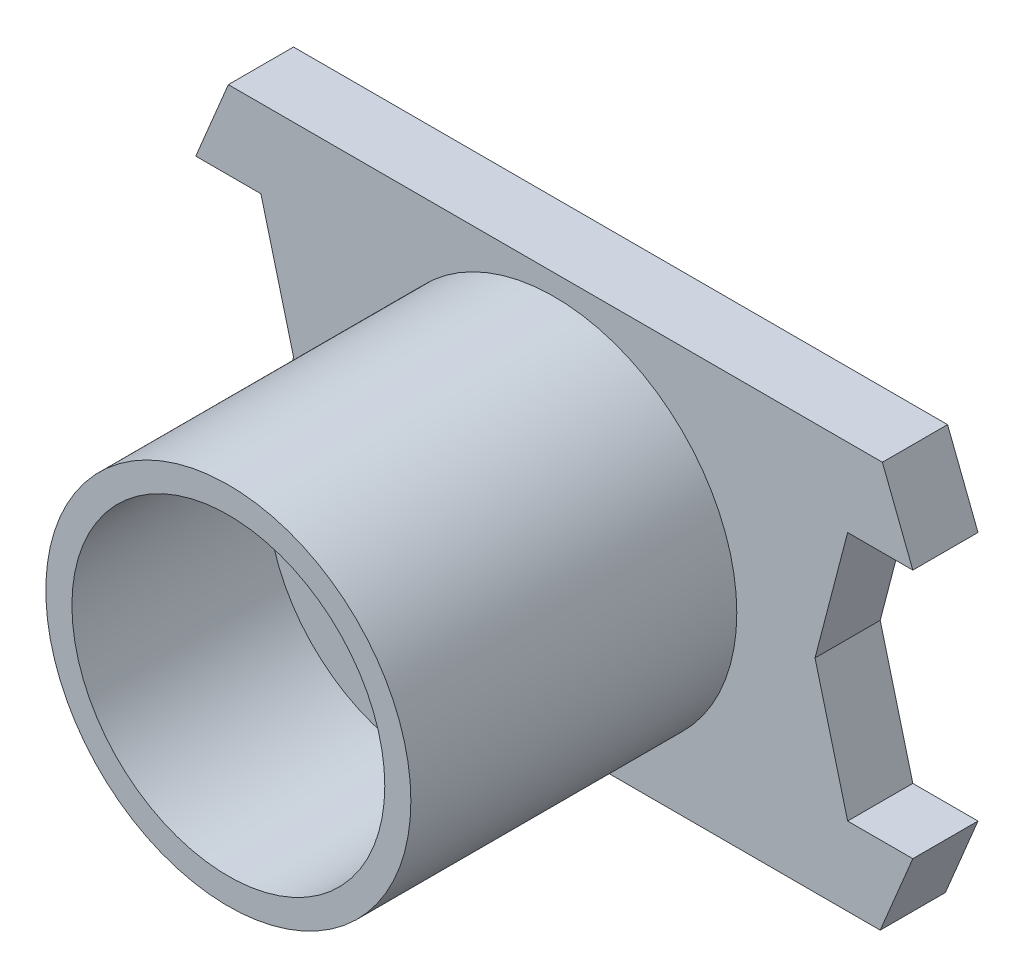
SolidWorks part; units mm, degrees
ref_plane "Спереди" through (0, 0, 0) normal (0, 0, 1) x (1, 0, 0)
ref_plane "Сверху" through (0, 0, 0) normal (0, 1, 0) x (1, 0, 0)
ref_plane "Справа" through (0, 0, 0) normal (1, 0, 0) x (0, 0, -1)
sketch "Эскиз1" plane through (0, 0, 0) normal (0, 0, 1) x (1, 0, 0)
  line L0 (-55, -19.1667) -> (-50, -31.1667)
  line L1 (-50, -31.1667) -> (50, -31.1667)
  line L2 (-55, -19.1667) -> (-55, 19.1667)
  line L3 (-50, 31.1667) -> (50.3333, 31.1667)
  line L4 (55, -19.1667) -> (55, 19.1667)
  line L5 (-50.9551, -28.8745) -> (51.176, 28.9997) construction
  line L6 (-50.9551, 28.8745) -> (50.9551, -28.8745) construction
  line L7 (-55, -19.1667) -> (-45, -19.1667)
  line L8 (-45, -19.1667) -> (-40, 0)
  line L9 (-40, 0) -> (-45, 19.1667)
  line L10 (-45, 19.1667) -> (-55, 19.1667)
  line L11 (-55, 19.1667) -> (-50, 31.1667)
  line L12 (50, -31.1667) -> (55, -19.1667)
  line L13 (55, -19.1667) -> (45, -19.1667)
  line L14 (45, -19.1667) -> (40, 0)
  line L15 (40, 0) -> (45, 19.1667)
  line L16 (45, 19.1667) -> (55, 19.1667)
  line L17 (55, 19.1667) -> (50.3333, 31.1667)
  point P0 (0, 0)
  dimension "D1" = 12
  dimension "D3" = 10
  dimension "D4" = 15
  dimension "D5" = 10
  dimension "D6" = 12
  dimension "D9" = 10
  dimension "D10" = 15
extrude "Бобышка-Вытянуть1" add sketch "Эскиз1" along normal blind 10 contours L16 L17 L3 L11 L10 L9 L8 L7 L0 L1 L12 L13 L14 L15
sketch "Эскиз2" plane through (0, 0, 10) normal (0, 0, 1) x (1, 0, 0)
  circle A0 centre (0, 0) radius 28
extrude "Бобышка-Вытянуть2" add sketch "Эскиз2" along normal blind 50
sketch "Эскиз3" plane through (0, 0, 60) normal (0, 0, 1) x (1, 0, 0)
  circle A0 centre (0, 0) radius 24
extrude "Вырез-Вытянуть1" cut sketch "Эскиз3" against normal blind 30
sketch "Эскиз4" plane through (0, 0, 30) normal (0, 0, 1) x (1, 0, 0)
  circle A0 centre (0, 0) radius 10
extrude "Вырез-Вытянуть2" cut sketch "Эскиз4" against normal blind 60
